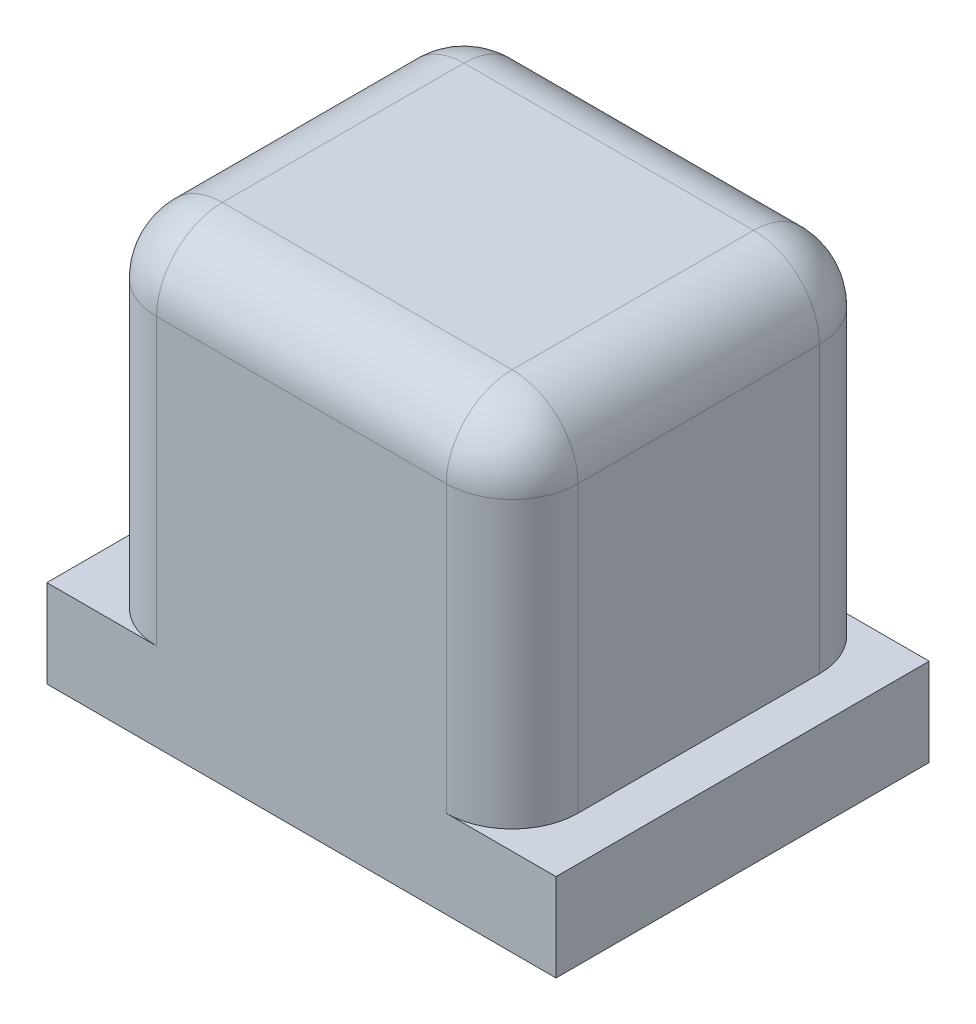
SolidWorks part; units mm, degrees
ref_plane "Front Plane" through (0, 0, 0) normal (0, 0, 1) x (1, 0, 0)
ref_plane "Top Plane" through (0, 0, 0) normal (0, 1, 0) x (1, 0, 0)
ref_plane "Right Plane" through (0, 0, 0) normal (1, 0, 0) x (0, 0, -1)
sketch "Sketch2" plane through (0, 0, 0) normal (0, 0, 1) x (1, 0, 0)
  line L0 (-12.75, 51.25) -> (-12.75, 53.25) construction
  line L1 (-12.55, 55.75) -> (-2.95, 55.75)
  line L2 (-12.55, 55.75) -> (-12.55, 45.75)
  line L3 (-12.55, 45.75) -> (-2.95, 45.75)
  line L4 (-2.95, 55.75) -> (-2.95, 45.75)
  line L5 (-2.75, 51.25) -> (-2.75, 53.25) construction
  line L6 (-9.75, 45.75) -> (-5.75, 45.75) construction
  line L7 (-7.75, 55.75) -> (-7.75, 45.75) construction
  line L8 (-2.95, 45.75) -> (-1.95, 45.75)
  line L9 (-2.95, 45.75) -> (-2.95, 47.75)
  line L10 (-2.95, 47.75) -> (-1.95, 47.75)
  line L11 (-1.95, 45.75) -> (-1.95, 47.75)
  line L12 (-12.55, 47.75) -> (-13.55, 47.75)
  line L13 (-13.55, 45.75) -> (-13.55, 47.75)
  line L14 (-12.55, 45.75) -> (-13.55, 45.75)
  line L15 (-12.55, 45.75) -> (-12.55, 47.75)
  dimension "D1" = 0.2
  dimension "D2" = 0.2
  dimension "D3" = 10
  dimension "D4" = 1
  dimension "D5" = 2
extrude "Boss-Extrude1" add sketch "Sketch2" along normal blind 8.5 contours L1 L7 L3 L4 | L7 L1 L2 L3 | L8 L11 L10 L4 | L14 L2 L12 L13
fillet "Fillet1" radius 1.5 8 edges at (-2.95, 51.75, 0) (-2.95, 51.75, 8.5) (-12.55, 51.75, 0) (-12.55, 51.75, 8.5) (-12.55, 55.75, 4.25) (-7.75, 55.75, 0) (-7.75, 55.75, 8.5) (-2.95, 55.75, 4.25)
